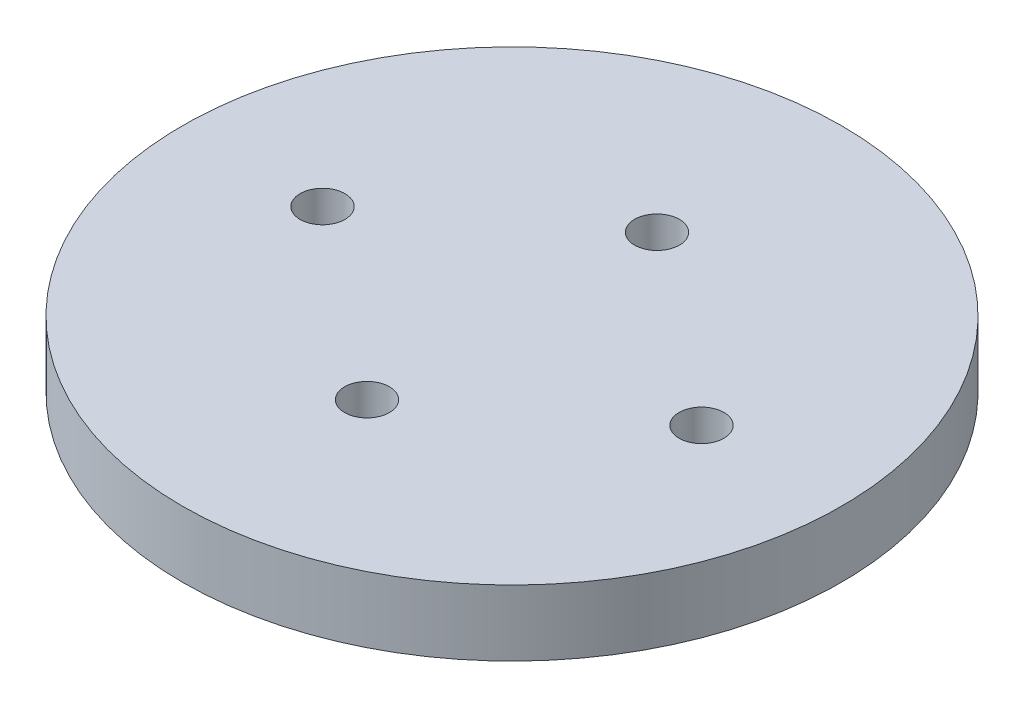
SolidWorks part; units mm, degrees
material "1060 Alloy"
ref_plane "Front Plane" through (0, 0, 0) normal (0, 0, 1) x (1, 0, 0)
ref_plane "Top Plane" through (0, 0, 0) normal (0, 1, 0) x (1, 0, 0)
ref_plane "Right Plane" through (0, 0, 0) normal (1, 0, 0) x (0, 0, -1)
sketch "Sketch1" plane through (0, 0, 0) normal (0, 1, 0) x (1, 0, 0)
  line L1 (57.825, 46.5) -> (-57.825, 46.5) construction
  line L2 (57.825, 46.5) -> (57.825, -46.5) construction
  line L3 (57.825, -46.5) -> (-57.825, -46.5) construction
  line L4 (-57.825, 46.5) -> (-57.825, -46.5) construction
  line L5 (-57.825, 46.5) -> (57.825, -46.5) construction
  line L6 (-57.825, 26.7384) -> (-42.825, 26.7384) construction
  line L36 (-42.825, 26.7384) -> (-9.5745, 0) construction
  line L37 (-9.5745, 0) -> (-42.825, -26.7384) construction
  line L38 (-42.825, -26.7384) -> (-57.825, -26.7384) construction
  line L39 (-57.825, -26.7384) -> (-57.825, -46.5) construction
  line L40 (-57.825, -46.5) -> (-33.2505, -46.5) construction
  line L41 (-33.2505, -46.5) -> (-33.2505, -34.4377) construction
  line L42 (-33.2505, -34.4377) -> (0, -7.6993) construction
  line L43 (0, -7.6993) -> (33.2505, -34.4377) construction
  line L44 (33.2505, -34.4377) -> (33.2505, -46.5) construction
  line L45 (33.2505, -46.5) -> (57.825, -46.5) construction
  line L46 (57.825, -46.5) -> (57.825, -26.7384) construction
  line L47 (57.825, -26.7384) -> (42.825, -26.7384) construction
  line L48 (42.825, -26.7384) -> (9.5745, 0) construction
  line L49 (9.5745, 0) -> (42.825, 26.7384) construction
  line L50 (42.825, 26.7384) -> (57.825, 26.7384) construction
  line L51 (57.825, 26.7384) -> (57.825, 46.5) construction
  line L52 (57.825, 46.5) -> (33.2505, 46.5) construction
  line L53 (33.2505, 46.5) -> (33.2505, 34.4377) construction
  line L54 (33.2505, 34.4377) -> (0, 7.6993) construction
  line L55 (0, 7.6993) -> (-33.2505, 34.4377) construction
  line L56 (-33.2505, 34.4377) -> (-33.2505, 46.5) construction
  line L57 (-33.2505, 46.5) -> (-57.825, 46.5) construction
  line L58 (-57.825, 46.5) -> (-57.825, 26.7384) construction
  line L59 (-57.825, -46.5) -> (57.825, 46.5) construction
  line L64 (42.825, 26.7384) -> (42.825, 34.4377)
  line L65 (42.825, 26.7384) -> (33.2505, 34.4377) construction
  line L66 (42.825, 34.4377) -> (33.2505, 34.4377)
  line L67 (33.2505, 34.4377) -> (-33.2505, 34.4377)
  line L68 (-33.2505, 34.4377) -> (-42.825, 34.4377)
  line L69 (-42.825, 34.4377) -> (-42.825, 26.7384)
  line L70 (-42.825, 26.7384) -> (-42.825, -26.7384)
  line L71 (-42.825, -26.7384) -> (-42.825, -34.4377)
  line L72 (-42.825, -34.4377) -> (-33.2505, -34.4377)
  line L73 (-33.2505, -34.4377) -> (33.2505, -34.4377)
  line L74 (33.2505, -34.4377) -> (42.825, -34.4377)
  line L75 (42.825, -34.4377) -> (42.825, -26.7384)
  line L78 (42.825, -26.7384) -> (42.825, 26.7384)
  line L79 (-9.5745, 0) -> (9.5745, 0) construction
  line L80 (0, 7.6993) -> (0, -7.6993) construction
  circle A1 centre (0, 11) radius 1.7
  circle A3 centre (-14.375, 0) radius 1.7
  circle A4 centre (0, 0) radius 25
  circle A5 centre (0, -11) radius 1.7
  circle A6 centre (14.375, 0) radius 1.7
  dimension "D6" = 3.4
  dimension "D8" = 3.4
  dimension "D9" = 50
  dimension "D1" = 115.65
  dimension "D2" = 93
  dimension "D3" = 12
  dimension "D4" = 15
  dimension "D10" = 11
  dimension "D5" = 28.75
extrude "Boss-Extrude1" add sketch "Sketch1" along normal blind 5 contours A4 A5 A1 A6 A3
equation "\"L1L\"=500"
equation "\"L1Thick\"=6.35"
equation "\"Harm-Drive-Outer\"=74.5"
equation "\"L1-Spacing\"=115.65"
equation "\"L-Bracket-HoleToWall\"=12.5"
equation "\"L-Bracket-HoleToSide\"=11"
equation "\"Bracket-Hole-D\"=6.8"
equation "\"D1@Sketch1\"=\"L1-Spacing\""
